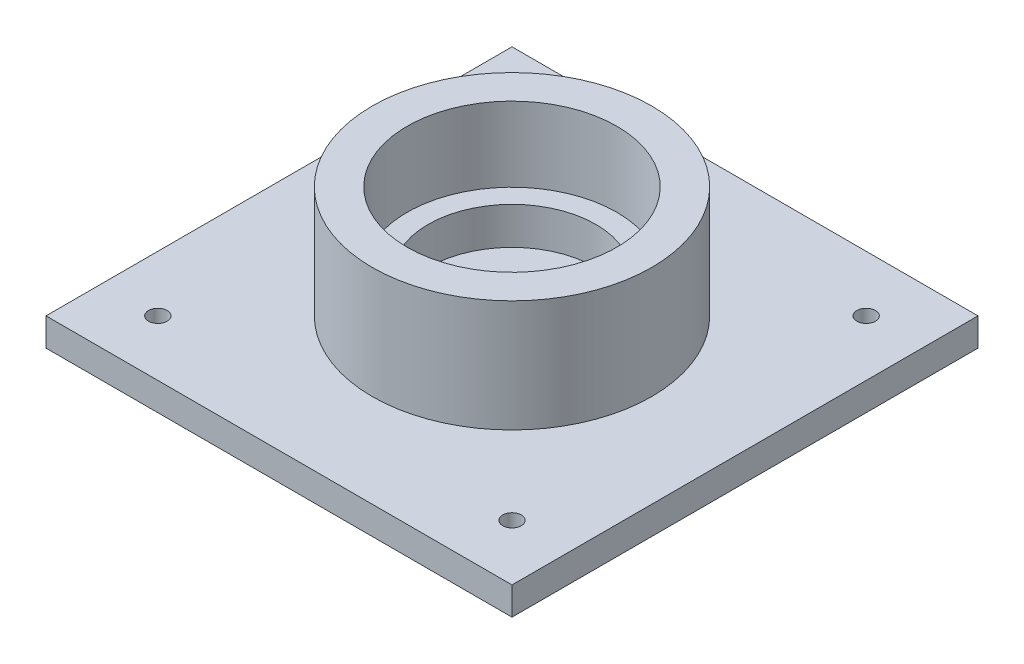
SolidWorks part; units mm, degrees
ref_plane "Front Plane" through (0, 0, 0) normal (0, 0, 1) x (1, 0, 0)
ref_plane "Top Plane" through (0, 0, 0) normal (0, 1, 0) x (1, 0, 0)
ref_plane "Right Plane" through (0, 0, 0) normal (1, 0, 0) x (0, 0, -1)
sketch "Sketch2" plane through (0, 0, 0) normal (0, 1, 0) x (1, 0, 0)
  line L1 (-25, 25) -> (25, 25)
  line L2 (-25, 25) -> (-25, -25)
  line L3 (-25, -25) -> (25, -25)
  line L4 (25, 25) -> (25, -25)
  point P4 (0, 25)
  point P6 (25, 0)
  dimension "D1" = 50
  dimension "D2" = 50
extrude "Boss-Extrude1" add sketch "Sketch2" along normal blind 15
sketch "Sketch3" plane through (0, 15, 0) normal (0, 1, 0) x (1, 0, 0)
  circle A0 centre (0, 0) radius 11.25
  dimension "D1" = 22.5
extrude "Cut-Extrude1" cut sketch "Sketch3" against normal blind 8
sketch "Sketch4" plane through (0, 7, 0) normal (0, 1, 0) x (1, 0, 0)
  circle A0 centre (0, 0) radius 9
  dimension "D1" = 18
extrude "Cut-Extrude2" cut sketch "Sketch4" against normal blind 4
sketch "Sketch5" plane through (0, 15, 0) normal (0, 1, 0) x (1, 0, 0)
  line L0 (-25, -25) -> (25, -25) construction
  line L1 (25, -25) -> (25, 25) construction
  line L2 (25, 25) -> (-25, 25) construction
  line L3 (-25, 25) -> (-25, -25) construction
  line L4 (-25, -25) -> (25, -25)
  line L5 (25, -25) -> (25, 25)
  line L6 (25, 25) -> (-25, 25)
  line L7 (-25, 25) -> (-25, -25)
  circle A0 centre (0, 0) radius 15
  dimension "D1" = 30
extrude "Cut-Extrude3" cut sketch "Sketch5" against normal offset from surface (12 mm away) 3 up to face at (0, 0, 0)
sketch "Sketch6" plane through (0, 3, 0) normal (0, 1, 0) x (1, 0, 0)
  line L0 (-25, -25) -> (-25, 25) construction
  line L1 (-25, 25) -> (25, 25) construction
  line L2 (25, -25) -> (-25, -25) construction
  line L3 (25, 25) -> (25, -25) construction
  circle A0 centre (-19, 19) radius 1
  circle A1 centre (19, 19) radius 1
  circle A2 centre (19, -19) radius 1
  circle A3 centre (-19, -19) radius 1
  point P8 (0, 0)
  point P9 (0, 0)
  point P10 (0, 0)
  point P11 (0, 0)
  point P12 (0, 0)
  dimension "D1" = 2
  dimension "D2" = 6
  dimension "D3" = 6
  dimension "D4" = 6
  dimension "D5" = 6
extrude "Cut-Extrude4" cut sketch "Sketch6" against normal through all both and the other way through all
